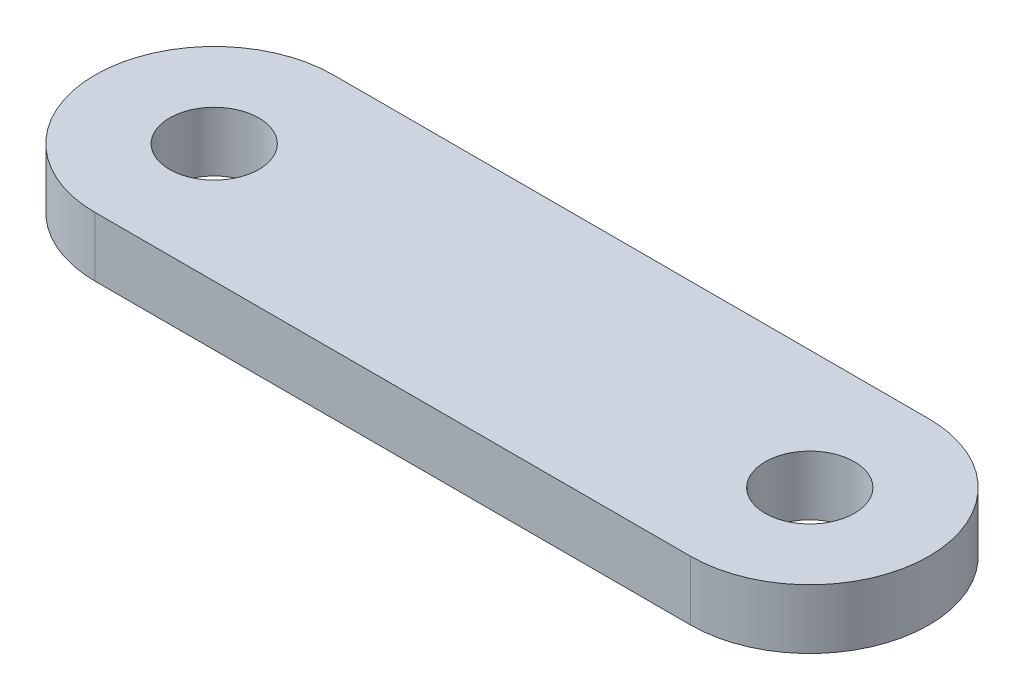
SolidWorks part; units mm, degrees
ref_plane "Front Plane" through (0, 0, 0) normal (0, 0, 1) x (1, 0, 0)
ref_plane "Top Plane" through (0, 0, 0) normal (0, 1, 0) x (1, 0, 0)
ref_plane "Right Plane" through (0, 0, 0) normal (1, 0, 0) x (0, 0, -1)
sketch "Sketch1" plane through (0, 0, 0) normal (0, 1, 0) x (1, 0, 0)
  line L0 (-12.7, 0) -> (12.7, 0) construction
  line L1 (-12.7, 5.08) -> (12.7, 5.08)
  line L2 (-12.7, -5.08) -> (12.7, -5.08)
  arc A0 (-12.7, 5.08) -> (-12.7, -5.08) centre (-12.7, 0) ccw
  arc A1 (12.7, -5.08) -> (12.7, 5.08) centre (12.7, 0) ccw
  circle A2 centre (-12.7, 0) radius 1.905
  circle A3 centre (12.7, 0) radius 1.905
  point P2 (0, 0)
  dimension "D2" = 3.81
  dimension "D3" = 3.175
  dimension "D1" = 25.4
extrude "Boss-Extrude1" add sketch "Sketch1" along normal blind 2.54
